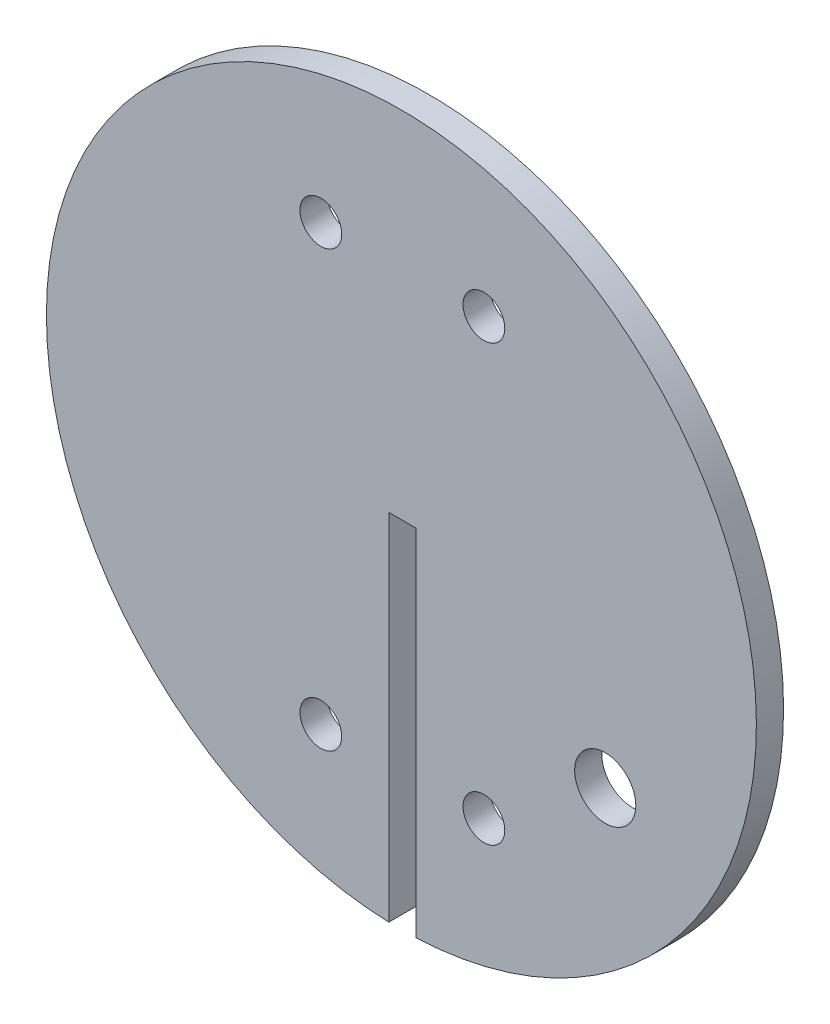
SolidWorks part; units mm, degrees
ref_plane "Front Plane" through (0, 0, 0) normal (0, 0, 1) x (1, 0, 0)
ref_plane "Top Plane" through (0, 0, 0) normal (0, 1, 0) x (1, 0, 0)
ref_plane "Right Plane" through (0, 0, 0) normal (1, 0, 0) x (0, 0, -1)
sketch "Sketch1" plane through (0, 0, 0) normal (0, 0, 1) x (1, 0, 0)
  circle A0 centre (0, 0) radius 66.3575
extrude "Boss-Extrude1" add sketch "Sketch1" along normal blind 5.08
sketch "Sketch3" plane through (0, 0, 0) normal (0, 0, 1) x (1, 0, 0)
  line L0 (0, 0) -> (66.3575, 0) construction
  line L1 (2.7181, -67.8586) -> (-2.3619, -67.8586)
  line L2 (2.7181, -67.8586) -> (2.7181, 0.0229)
  line L3 (2.7181, 0.0229) -> (-2.3619, 0.0229)
  line L4 (-2.3619, -67.8586) -> (-2.3619, 0.0229)
  line L5 (2.7181, -67.8586) -> (-2.3619, 0.0229) construction
  line L6 (2.7181, 0.0229) -> (-2.3619, -67.8586) construction
  line L7 (66.3575, 0) -> (-66.3575, 0) construction
  line L8 (-53.6575, 0) -> (-66.3575, 0)
  line L9 (-41.104, -34.4904) -> (-50.8328, -42.6538)
  line L10 (41.104, 34.4904) -> (50.8328, 42.6538)
  line L11 (53.6575, 0) -> (66.3575, 0)
  circle A0 centre (0, 0) radius 19.05
  circle A1 centre (0, 0) radius 45.2265 construction
  circle A2 centre (-15.0619, -40.64) radius 3.9006
  circle A3 centre (15.4181, -40.64) radius 3.9006
  circle A4 centre (0, 0) radius 66.3575 construction
  circle A5 centre (15.4181, 40.64) radius 3.9006
  circle A6 centre (-15.0619, 40.64) radius 3.9006
  circle A7 centre (38.1, -24.3685) radius 5.715
  arc A8 (-41.104, -34.4904) -> (-53.6575, 0) centre (0, 0) cw
  circle A9 centre (0, 0) radius 53.6575
  circle A10 centre (0, 0) radius 53.6575 construction
  arc A11 (41.104, 34.4904) -> (53.6575, 0) centre (0, 0) cw
  arc A12 (-66.3575, 0) -> (-50.7671, -42.732) centre (0, 0) ccw
  arc A13 (50.8328, 42.6538) -> (66.3575, 0) centre (0, 0) cw
  point P3 (0.1781, -33.9179)
  point P31 (0, 0)
  dimension "D1" = 5.08
  dimension "D4" = 40.64
  dimension "D8" = 38.1
  dimension "D2" = 12.7
  dimension "D3" = 12.7
  dimension "D5" = 40.64
  dimension "D9" = 67.8815
  dimension "D7" = 2
  dimension "D6" = 12.7
extrude "Cut-Extrude2" cut sketch "Sketch3" along normal up to next contours A3 | A2 | A5 | A6 | L2 L3 L4 L1 | A7
